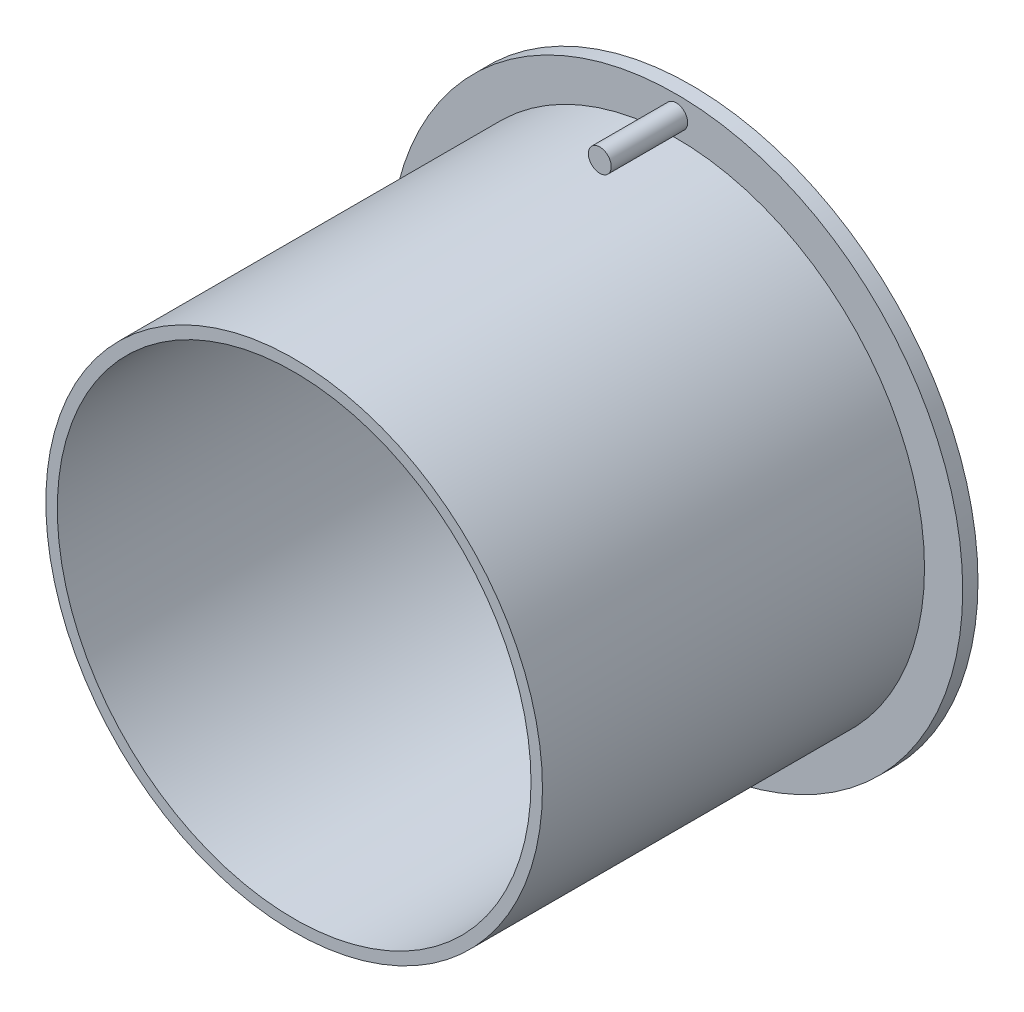
SolidWorks part; units mm, degrees
material "1060 Alloy"
ref_plane "Front Plane" through (0, 0, 0) normal (0, 0, 1) x (1, 0, 0)
ref_plane "Top Plane" through (0, 0, 0) normal (0, 1, 0) x (1, 0, 0)
ref_plane "Right Plane" through (0, 0, 0) normal (1, 0, 0) x (0, 0, -1)
sketch "Sketch1" plane through (0, 0, 0) normal (0, 0, 1) x (1, 0, 0)
  circle A0 centre (0, 0) radius 37.5
  circle A1 centre (0, 0) radius 32.5
  circle A2 centre (0, 0) radius 31
  dimension "D1" = 75
  dimension "D2" = 65
  dimension "D3" = 62
extrude "Boss-Extrude1" add sketch "Sketch1" against normal blind 2 contours A0 A1 | A1 A2 | A2
sketch "Sketch2" plane through (0, 0, 0) normal (0, 0, 1) x (1, 0, 0)
  circle A0 centre (0, 0) radius 32.5
  circle A1 centre (0, 0) radius 31
  dimension "D1" = 65
  dimension "D2" = 62
extrude "Boss-Extrude2" add sketch "Sketch2" along normal blind 55
sketch "Sketch3" plane through (0, 0, -2) normal (0, 0, -1) x (-1, 0, 0)
  line L0 (0, 37.5) -> (0, 32.5)
  line L1 (0, -32.5) -> (0, -37.5)
  line L2 (0, 37.5) -> (0, 35)
  line L3 (0, 35) -> (6.0304, 35)
  line L4 (0, -35) -> (6.0304, -35)
  circle A0 centre (0, 0) radius 32.5
  circle A3 centre (0, 0) radius 37.5 construction
  dimension "D1" = 65
sketch "Sketch8" plane through (0, 0, 0) normal (0, 0, 1) x (1, 0, 0)
  circle A2 centre (0, 35) radius 1.5
  circle A3 centre (0, -35) radius 1.5
  dimension "D1" = 3
  dimension "D2" = 3
extrude "Boss-Extrude3" add sketch "Sketch8" along normal blind 10
sketch "Sketch9" plane through (0, 0, 55) normal (0, 0, 1) x (1, 0, 0)
  circle A0 centre (0, 0) radius 32.5
  circle A1 centre (0, 0) radius 31
extrude "Cut-Extrude1" cut sketch "Sketch9" against normal blind 5
sketch "Sketch10" plane through (0, 0, -2) normal (0, 0, -1) x (-1, 0, 0)
  line L1 (0, 32.5) -> (0, 16.96)
  circle A1 centre (0, 16.96) radius 12.5
  dimension "D4" = 25
  dimension "D3" = 15.54
extrude "Cut-Extrude3" cut sketch "Sketch10" against normal blind 100
